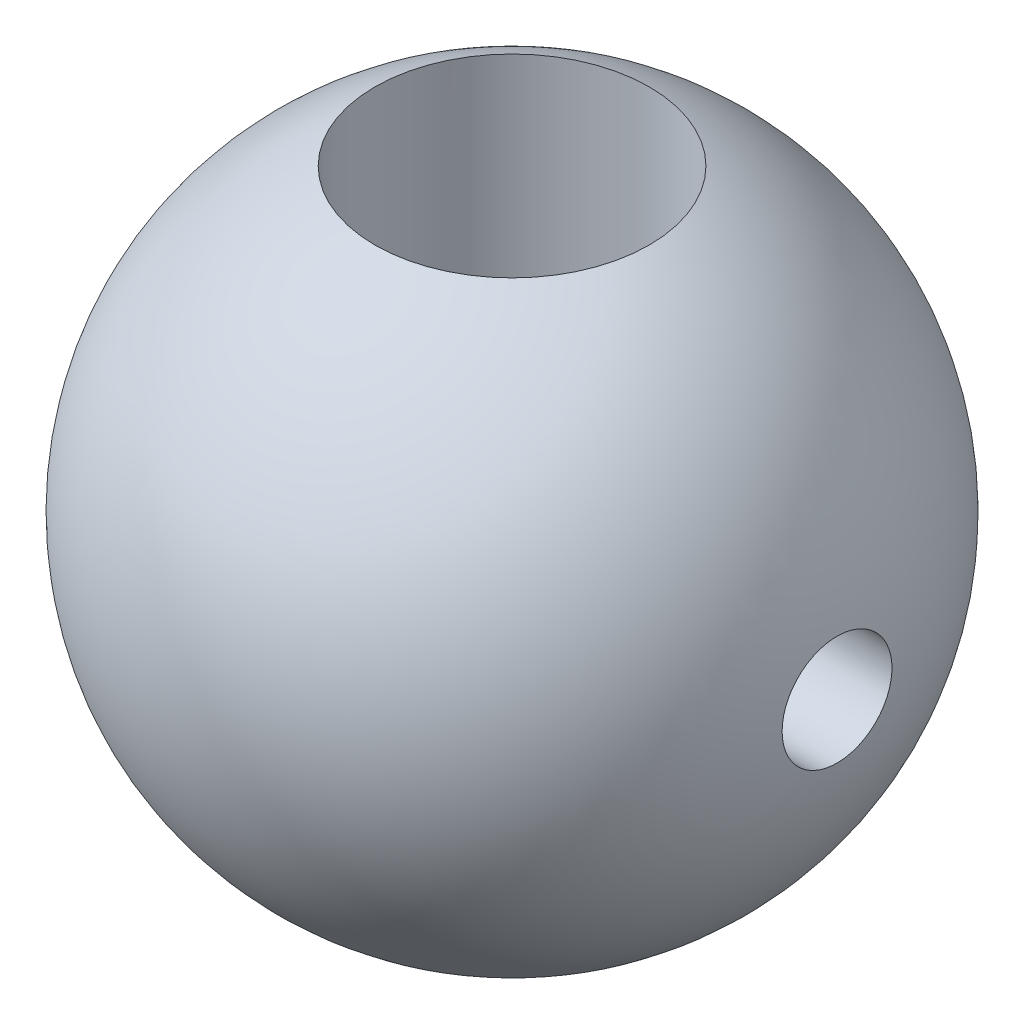
SolidWorks part; units mm, degrees
material "Chrome Stainless Steel"
ref_plane "Front Plane" through (0, 0, 0) normal (0, 0, 1) x (1, 0, 0)
ref_plane "Top Plane" through (0, 0, 0) normal (0, 1, 0) x (1, 0, 0)
ref_plane "Right Plane" through (0, 0, 0) normal (1, 0, 0) x (0, 0, -1)
sketch "Sketch1" plane through (0, 0, 0) normal (0, 0, 1) x (1, 0, 0)
  line L0 (0, 11.2382) -> (0, -12.8433) construction
  line L1 (3.9624, 8.6617) -> (3.9624, -8.6617)
  arc A0 (3.9624, -8.6617) -> (3.9624, 8.6617) centre (0, 0) ccw
  point P1 (0, -12.8433)
  point P4 (0, 11.2382)
  dimension "D1" = 9.525
  dimension "D2" = 3.9624
revolve "Revolve1" add sketch "Sketch1" angle 360 about L0
sketch "Sketch2" plane through (0, 0, 0) normal (0, 0, 1) x (1, 0, 0)
  line L1 (-12.1936, 0) -> (12.8839, 0)
  line L2 (-12.1936, 0) -> (-12.1936, 1.5875)
  line L3 (-12.1936, 1.5875) -> (12.8839, 1.5875)
  line L4 (12.8839, 0) -> (12.8839, 1.5875)
  dimension "D1" = 1.5875
revolve "Cut-Revolve1" cut sketch "Sketch2" angle 360 about L1
